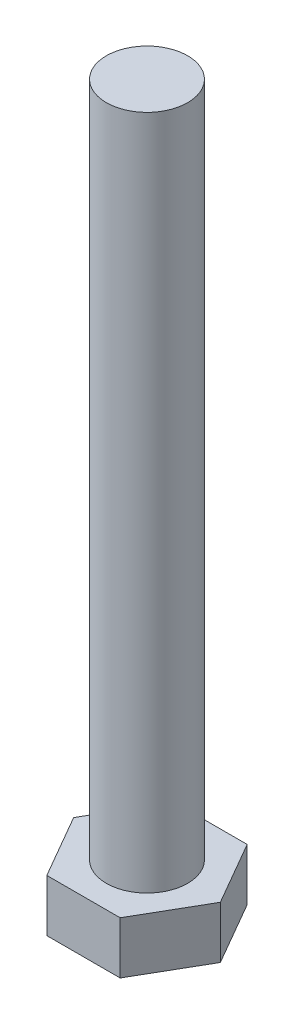
SolidWorks part; units mm, degrees
ref_plane "Front Plane" through (0, 0, 0) normal (0, 0, 1) x (1, 0, 0)
ref_plane "Top Plane" through (0, 0, 0) normal (0, 1, 0) x (1, 0, 0)
ref_plane "Right Plane" through (0, 0, 0) normal (1, 0, 0) x (0, 0, -1)
sketch "Sketch1" plane through (0, 0, 0) normal (0, 1, 0) x (1, 0, 0)
  line L1 (-10.8253, 0) -> (-5.4127, -9.375)
  line L2 (-5.4127, -9.375) -> (5.4127, -9.375)
  line L3 (5.4127, -9.375) -> (10.8253, 0)
  line L4 (10.8253, 0) -> (5.4127, 9.375)
  line L5 (5.4127, 9.375) -> (-5.4127, 9.375)
  line L6 (-5.4127, 9.375) -> (-10.8253, 0)
  circle A0 centre (0, 0) radius 9.375 construction
  dimension "D1" = 18.75
extrude "Boss-Extrude1" add sketch "Sketch1" along normal blind 7.7
sketch "Sketch2" plane through (0, 7.7, 0) normal (0, 1, 0) x (1, 0, 0)
  circle A0 centre (0, 0) radius 6
  dimension "D1" = 12
extrude "Boss-Extrude2" add sketch "Sketch2" along normal blind 99.8
